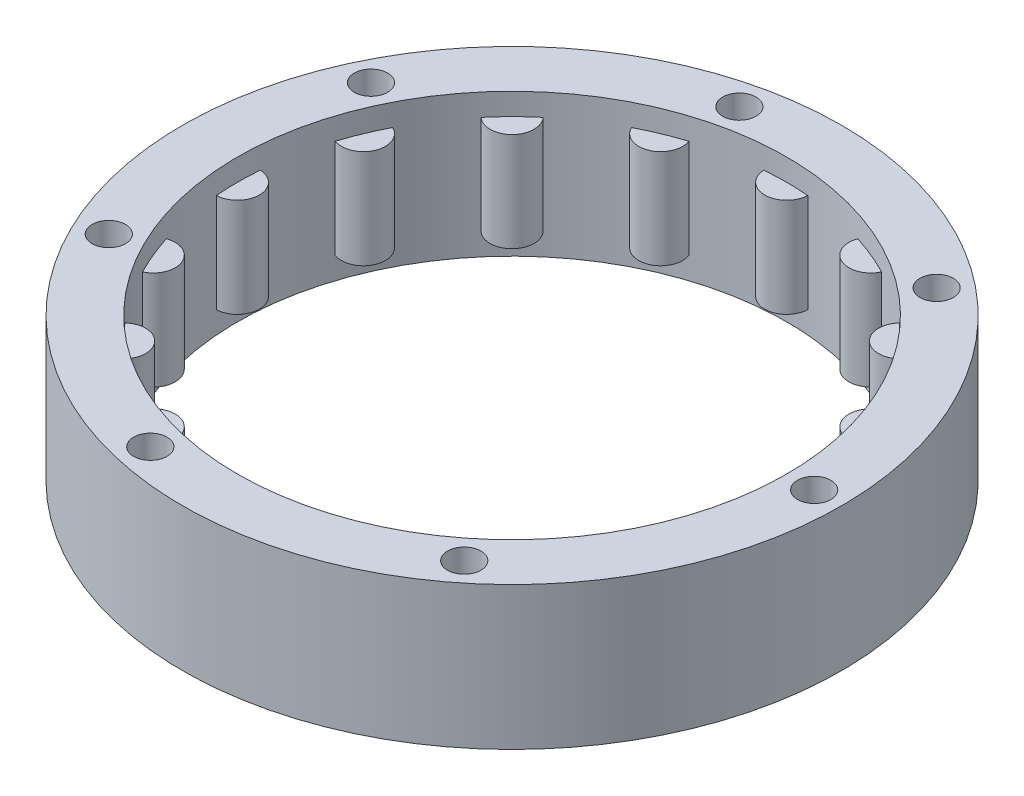
SolidWorks part; units mm, degrees
ref_plane "Alzado" through (0, 0, 0) normal (0, 0, 1) x (1, 0, 0)
ref_plane "Planta" through (0, 0, 0) normal (0, 1, 0) x (1, 0, 0)
ref_plane "Vista lateral" through (0, 0, 0) normal (1, 0, 0) x (0, 0, -1)
sketch "Croquis1" plane through (0, 0, 0) normal (0, 1, 0) x (1, 0, 0)
  circle A0 centre (0, 0) radius 25 construction
  circle A1 centre (25, 0) radius 2
  circle A2 centre (23.097, -9.5671) radius 2
  circle A3 centre (17.6777, -17.6777) radius 2
  circle A4 centre (9.5671, -23.097) radius 2
  circle A5 centre (0, -25) radius 2
  circle A6 centre (-9.5671, -23.097) radius 2
  circle A7 centre (-17.6777, -17.6777) radius 2
  circle A8 centre (-23.097, -9.5671) radius 2
  circle A9 centre (-25, 0) radius 2
  circle A10 centre (-23.097, 9.5671) radius 2
  circle A11 centre (-17.6777, 17.6777) radius 2
  circle A12 centre (-9.5671, 23.097) radius 2
  circle A13 centre (0, 25) radius 2
  circle A14 centre (9.5671, 23.097) radius 2
  circle A15 centre (17.6777, 17.6777) radius 2
  circle A16 centre (23.097, 9.5671) radius 2
  point P37 (0, 0)
  dimension "D1" = 50
  dimension "D2" = 4
  dimension "D3" = 16
extrude "Saliente-Extruir1" add sketch "Croquis1" along normal mid plane 9
sketch "Croquis3" plane through (0, 0, 0) normal (0, 1, 0) x (1, 0, 0)
  circle A0 centre (0, 0) radius 25
  circle A1 centre (0, 0) radius 30
  dimension "D1" = 60
extrude "Saliente-Extruir2" add sketch "Croquis3" along normal mid plane 13
sketch "Croquis4" plane through (0, 6.5, 0) normal (0, 1, 0) x (1, 0, 0)
  circle A0 centre (27.5, 0) radius 1.52
  circle A1 centre (17.146, -21.5004) radius 1.52
  circle A2 centre (-6.1193, -26.8105) radius 1.52
  circle A3 centre (-24.7766, -11.9318) radius 1.52
  circle A4 centre (-24.7766, 11.9318) radius 1.52
  circle A5 centre (-6.1193, 26.8105) radius 1.52
  circle A6 centre (17.146, 21.5004) radius 1.52
  point P17 (0, 0)
  dimension "D2" = 3.04
  dimension "D1" = 27.5
  dimension "D3" = 7
extrude "Cortar-Extruir1" cut sketch "Croquis4" against normal through all
